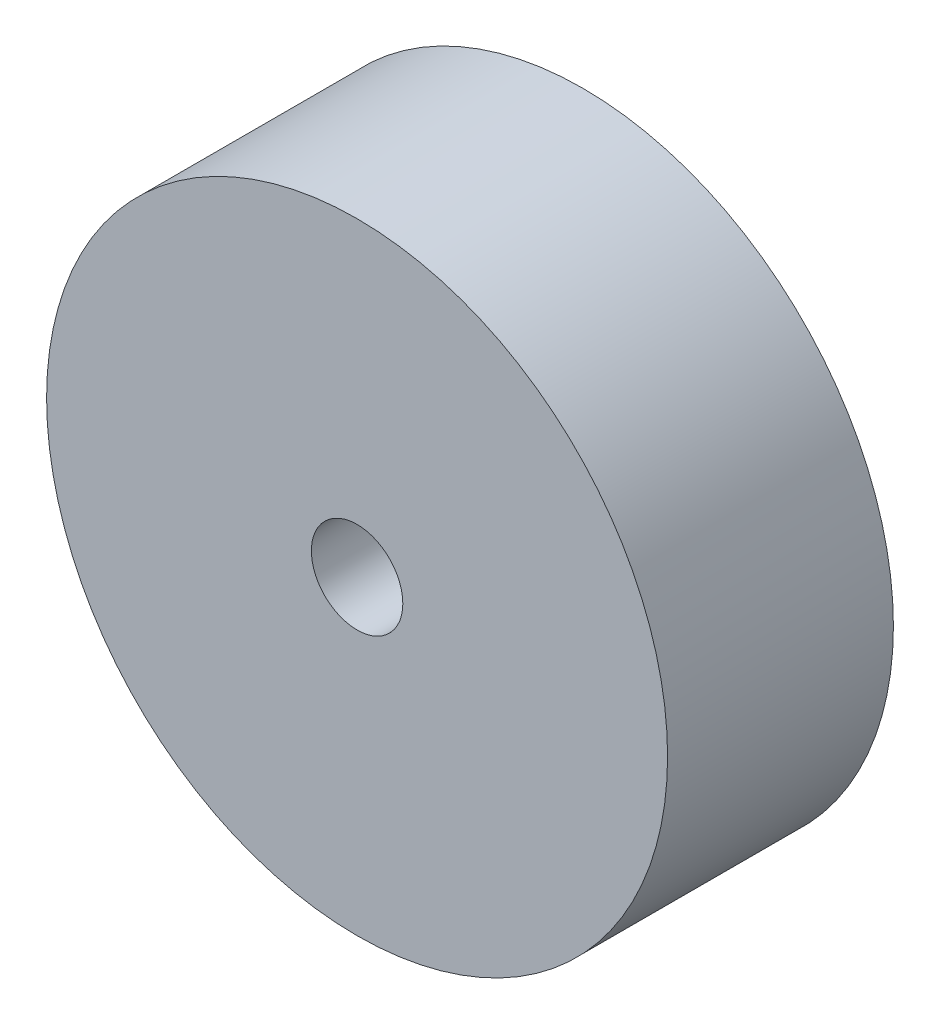
SolidWorks part; units mm, degrees
ref_plane "Alzado" through (0, 0, 0) normal (0, 0, 1) x (1, 0, 0)
ref_plane "Planta" through (0, 0, 0) normal (0, 1, 0) x (1, 0, 0)
ref_plane "Vista lateral" through (0, 0, 0) normal (1, 0, 0) x (0, 0, -1)
sketch "Croquis1" plane through (0, 0, 0) normal (0, 0, 1) x (1, 0, 0)
  circle A0 centre (0, 0) radius 27.5
  dimension "D1" = 55
extrude "Saliente-Extruir1" add sketch "Croquis1" along normal mid plane 20
sketch "Croquis4" plane through (0, 0, 10) normal (0, 0, 1) x (1, 0, 0)
  circle A0 centre (0, 0) radius 4.05
  dimension "D1" = 8.1
extrude "Cortar-Extruir2" cut sketch "Croquis4" against normal blind 108
